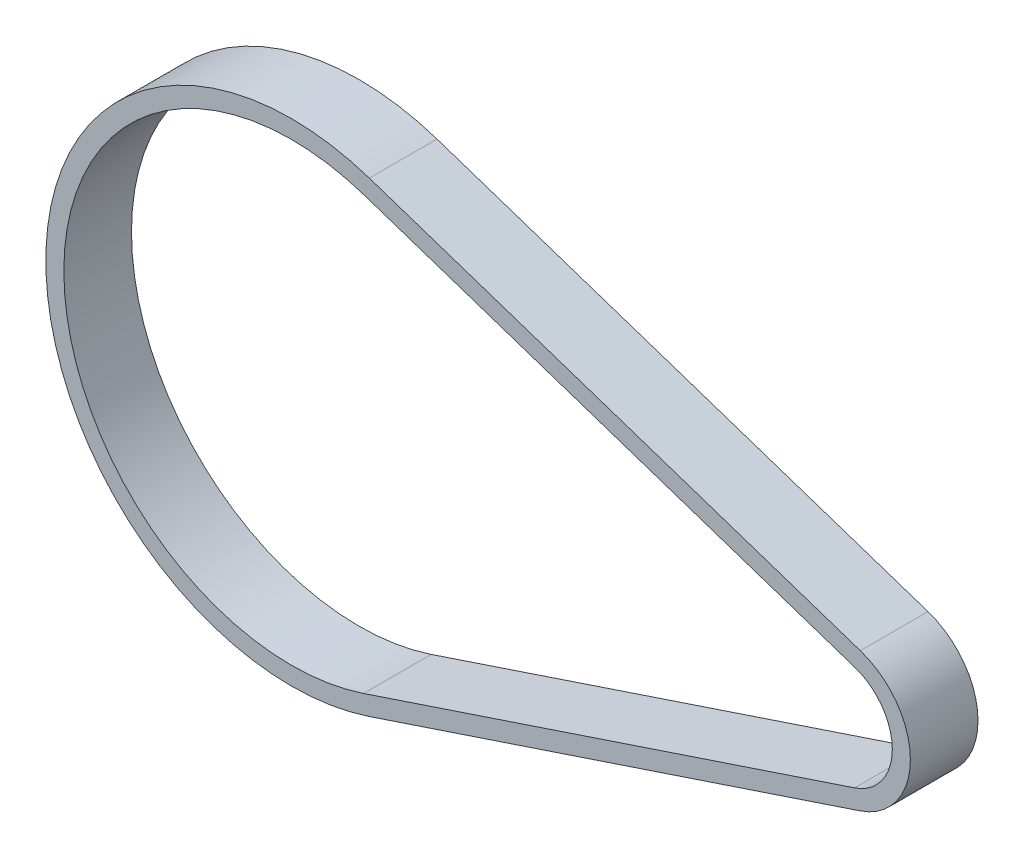
SolidWorks part; units mm, degrees
ref_plane "Front Plane" through (0, 0, 0) normal (0, 0, 1) x (1, 0, 0)
ref_plane "Top Plane" through (0, 0, 0) normal (0, 1, 0) x (1, 0, 0)
ref_plane "Right Plane" through (0, 0, 0) normal (1, 0, 0) x (0, 0, -1)
sketch "Sketch1" plane through (0, 0, 0) normal (0, 0, 1) x (1, 0, 0)
  line L0 (-22.75, 0) -> (37.75, 0) construction
  line L1 (-14.1291, 25.8504) -> (40.3157, 7.6935)
  line L2 (39.683, 5.7962) -> (-14.7618, 23.9531)
  line L3 (-14.7618, -23.9531) -> (39.683, -5.7962)
  line L4 (40.3157, -7.6935) -> (-14.1291, -25.8504)
  circle A0 centre (37.75, 0) radius 6.11 construction
  circle A1 centre (-22.75, 0) radius 25.25 construction
  circle A2 centre (-22.75, 0) radius 27.25 construction
  circle A3 centre (37.75, 0) radius 8.11 construction
  arc A4 (-14.1291, 25.8504) -> (-14.1291, -25.8504) centre (-22.75, 0) ccw
  arc A5 (-14.7618, 23.9531) -> (-14.7618, -23.9531) centre (-22.75, 0) ccw
  arc A6 (40.3157, 7.6935) -> (40.3157, -7.6935) centre (37.75, 0) cw
  arc A7 (39.683, 5.7962) -> (39.683, -5.7962) centre (37.75, 0) cw
  point P4 (0, 0)
  point P19 (0, 0)
extrude "Boss-Extrude1" add sketch "Sketch1" along normal blind 7.5
